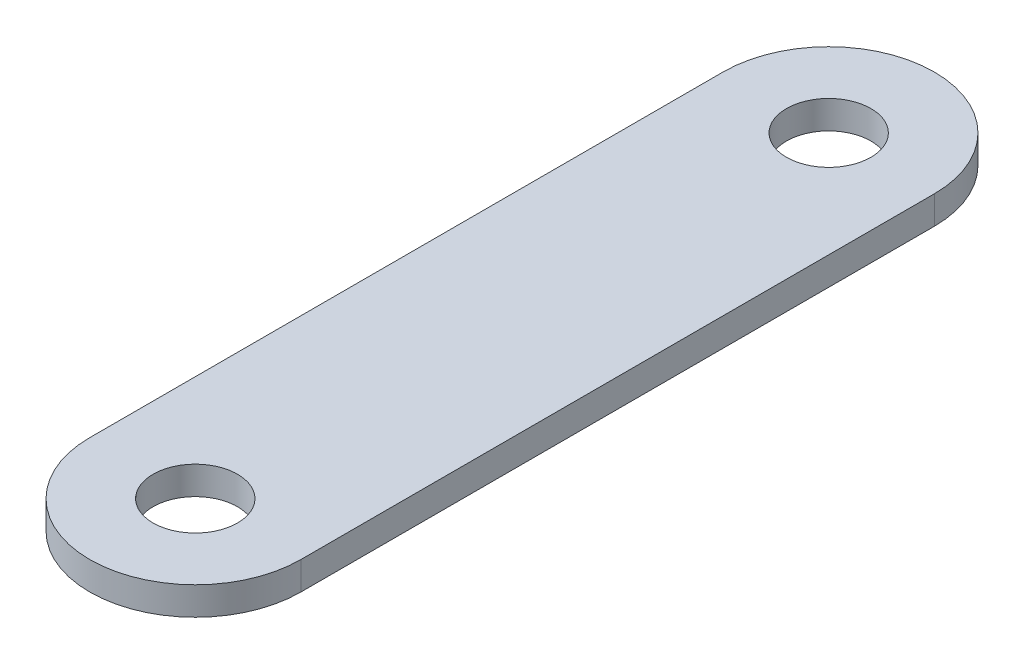
SolidWorks part; units mm, degrees
material "ASTM A36 Acero"
ref_plane "Front" through (0, 0, 0) normal (0, 0, 1) x (1, 0, 0)
ref_plane "Top" through (0, 0, 0) normal (0, 1, 0) x (1, 0, 0)
ref_plane "Right" through (0, 0, 0) normal (1, 0, 0) x (0, 0, -1)
sketch "Croquis1" plane through (0, 0, 0) normal (0, 1, 0) x (1, 0, 0)
  line L0 (0, 22.5) -> (0, -22.5) construction
  line L2 (-7.5, -22.5) -> (-7.5, 22.5)
  line L4 (7.5, -22.5) -> (7.5, 22.5)
  arc A0 (7.5, 22.5) -> (-7.5, 22.5) centre (0, 22.5) ccw
  arc A1 (-7.5, -22.5) -> (7.5, -22.5) centre (0, -22.5) ccw
  circle A2 centre (0, 22.5) radius 3
  circle A3 centre (0, -22.5) radius 3
  dimension "D2" = 6
  dimension "D1" = 45
  dimension "D3" = 15
extrude "Saliente-Extruir1" add sketch "Croquis1" along normal blind 2
